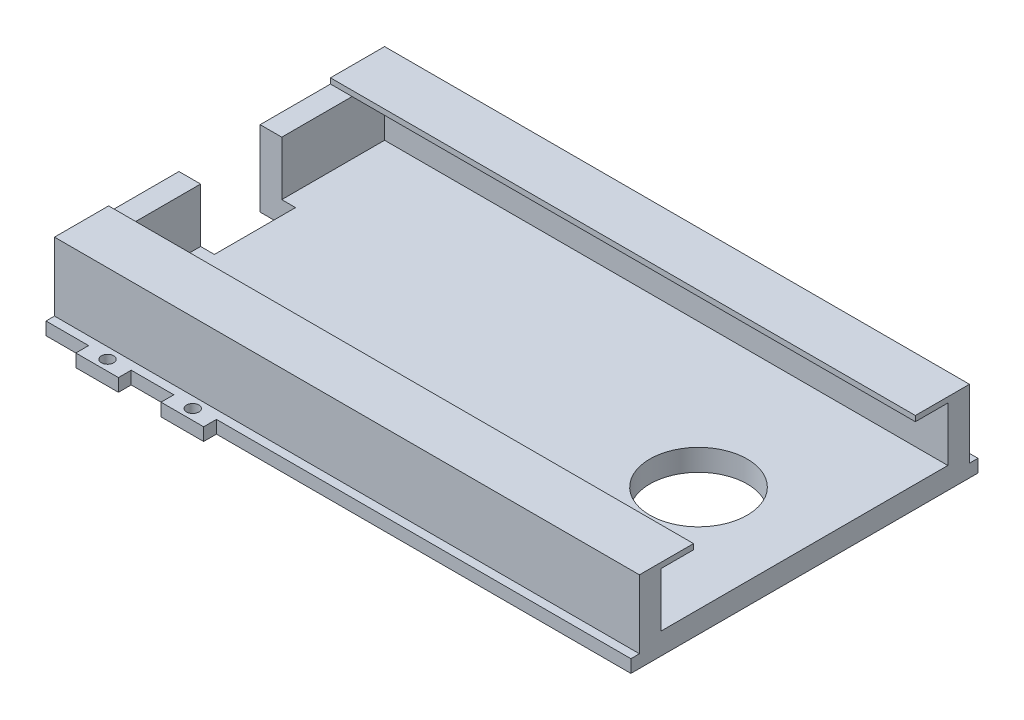
SolidWorks part; units mm, degrees
ref_plane "Front Plane" through (0, 0, 0) normal (0, 0, 1) x (1, 0, 0)
ref_plane "Top Plane" through (0, 0, 0) normal (0, 1, 0) x (1, 0, 0)
ref_plane "Right Plane" through (0, 0, 0) normal (1, 0, 0) x (0, 0, -1)
sketch "Sketch1" plane through (0, 0, 0) normal (0, 1, 0) x (1, 0, 0)
  line L1 (68.6435, -38.735) -> (-68.6435, -38.735)
  line L2 (68.6435, -38.735) -> (68.6435, 38.735)
  line L3 (68.6435, 38.735) -> (-68.6435, 38.735)
  line L4 (-68.6435, -38.735) -> (-68.6435, 38.735)
  line L5 (0, 38.735) -> (0, -38.735) construction
  line L6 (68.6435, 0) -> (-68.6435, 0) construction
  point P0 (0, 0)
extrude "Boss-Extrude1" add sketch "Sketch1" along normal blind 17.78
sketch "Sketch2" plane through (0, 17.78, 0) normal (0, 1, 0) x (1, 0, 0)
  line L0 (68.6435, -38.735) -> (68.6435, 38.735) construction
  line L1 (-63.5635, 33.655) -> (68.6435, 33.655)
  line L2 (-63.5635, 33.655) -> (-63.5635, -33.655)
  line L3 (-63.5635, -33.655) -> (68.6435, -33.655)
  line L4 (68.6435, 33.655) -> (68.6435, -33.655)
  line L5 (-68.6435, 38.735) -> (-68.6435, -38.735) construction
  line L6 (68.6435, 38.735) -> (-68.6435, 38.735) construction
  line L7 (-68.6435, -38.735) -> (68.6435, -38.735) construction
  dimension "D1" = 0
  dimension "D2" = 5.08
  dimension "D3" = 5.08
  dimension "D4" = 5.08
extrude "Cut-Extrude1" cut sketch "Sketch2" against normal blind 12.7
sketch "Sketch4" plane through (0, 5.08, 0) normal (0, 1, 0) x (1, 0, 0)
  line L0 (-63.5635, 33.655) -> (-63.5635, -33.655) construction
  circle A0 centre (43.7769, 0) radius 11.43
  dimension "D1" = 107.3404
extrude "Cut-Extrude2" cut sketch "Sketch4" against normal through all contours A0
sketch "Sketch5" plane through (0, 17.78, 0) normal (0, 1, 0) x (1, 0, 0)
  line L0 (68.6435, -33.655) -> (68.6435, 33.655) construction
  line L1 (-68.6435, 38.735) -> (68.6435, 38.735)
  line L2 (-68.6435, 38.735) -> (-68.6435, 26.035)
  line L3 (-68.6435, 26.035) -> (68.6435, 26.035)
  line L4 (68.6435, 38.735) -> (68.6435, 26.035)
  line L5 (-68.6435, 38.735) -> (-68.6435, -38.735) construction
  line L6 (68.6435, -38.735) -> (-68.6435, -38.735)
  line L7 (68.6435, -38.735) -> (68.6435, -26.035)
  line L8 (68.6435, -26.035) -> (-68.6435, -26.035)
  line L9 (-68.6435, -38.735) -> (-68.6435, -26.035)
  dimension "D1" = 12.7
  dimension "D2" = 12.7
extrude "Boss-Extrude2" add sketch "Sketch5" along normal blind 1.27
sketch "Sketch6" plane through (0, 17.78, 0) normal (0, 1, 0) x (1, 0, 0)
  line L0 (-68.6435, 26.035) -> (-68.6435, -26.035) construction
  line L1 (-68.6435, 9.525) -> (-60.3292, 9.525)
  line L2 (-68.6435, 9.525) -> (-68.6435, -9.525)
  line L3 (-68.6435, -9.525) -> (-60.3292, -9.525)
  line L4 (-60.3292, 9.525) -> (-60.3292, -9.525)
  line L5 (68.6435, 38.735) -> (-68.6435, 38.735) construction
  line L6 (-68.6435, -38.735) -> (68.6435, -38.735) construction
  dimension "D1" = 29.21
  dimension "D2" = 29.21
extrude "Cut-Extrude3" cut sketch "Sketch6" against normal through all
sketch "Sketch9" plane through (0, 0, 0) normal (0, -1, 0) x (-1, 0, 0)
  line L0 (68.6435, -9.525) -> (68.6435, -38.735) construction
  line L1 (-68.6435, -38.735) -> (68.6435, -38.735)
  line L2 (-68.6435, -38.735) -> (-68.6435, -40.735)
  line L3 (-68.6435, -40.735) -> (68.6435, -40.735)
  line L4 (68.6435, -38.735) -> (68.6435, -40.735)
  line L5 (68.6435, 38.735) -> (-68.6435, 38.735)
  line L6 (68.6435, 38.735) -> (68.6435, 40.735)
  line L7 (68.6435, 40.735) -> (-68.6435, 40.735)
  line L8 (-68.6435, 38.735) -> (-68.6435, 40.735)
  line L9 (58.6435, -40.735) -> (48.6435, -40.735)
  line L10 (58.6435, -40.735) -> (58.6435, -43.735)
  line L11 (58.6435, -43.735) -> (48.6435, -43.735)
  line L12 (48.6435, -40.735) -> (48.6435, -43.735)
  line L13 (58.6435, 40.735) -> (48.6435, 40.735)
  line L14 (58.6435, 40.735) -> (58.6435, 43.735)
  line L15 (58.6435, 43.735) -> (48.6435, 43.735)
  line L16 (48.6435, 40.735) -> (48.6435, 43.735)
  line L17 (38.6435, -40.735) -> (28.6435, -40.735)
  line L18 (38.6435, -40.735) -> (38.6435, -43.735)
  line L19 (38.6435, -43.735) -> (28.6435, -43.735)
  line L20 (28.6435, -40.735) -> (28.6435, -43.735)
  line L21 (38.6435, 40.735) -> (28.6435, 40.735)
  line L22 (38.6435, 40.735) -> (38.6435, 43.735)
  line L23 (38.6435, 43.735) -> (28.6435, 43.735)
  line L24 (28.6435, 40.735) -> (28.6435, 43.735)
  dimension "D1" = 2
  dimension "D2" = 2
  dimension "D3" = 10
  dimension "D4" = 10
  dimension "D5" = 10
  dimension "D6" = 10
  dimension "D7" = 10
  dimension "D8" = 10
  dimension "D9" = 10
  dimension "D10" = 10
  dimension "D11" = 3
  dimension "D12" = 3
  dimension "D13" = 3
  dimension "D14" = 3
extrude "Boss-Extrude4" add sketch "Sketch9" against normal blind 3 contours L23 L24 L21 L22 | L7 L8 L5 L6 | L15 L16 L13 L14 | L19 L20 L17 L18 | L11 L12 L9 L10 | L1 L4 L3 L2
sketch "Sketch10" plane through (0, 0, 0) normal (0, -1, 0) x (-1, 0, 0)
  line L0 (58.6435, 43.735) -> (48.6435, 43.735) construction
  line L1 (38.6435, 43.735) -> (28.6435, 43.735) construction
  line L2 (38.6435, -43.735) -> (28.6435, -43.735) construction
  line L3 (58.6435, -43.735) -> (48.6435, -43.735) construction
  line L4 (58.6435, -40.735) -> (58.6435, -43.735) construction
  line L5 (38.6435, -40.735) -> (38.6435, -43.735) construction
  line L6 (38.6435, 40.735) -> (38.6435, 43.735) construction
  line L7 (58.6435, 40.735) -> (58.6435, 43.735) construction
  circle A0 centre (33.6435, -41.295) radius 1.44
  circle A1 centre (53.6435, -41.295) radius 1.44
  circle A2 centre (53.6435, 41.295) radius 1.44
  circle A3 centre (33.6435, 41.295) radius 1.44
  dimension "D1" = 2.44
  dimension "D2" = 2.44
  dimension "D4" = 2.44
  dimension "D5" = 5
  dimension "D6" = 5
  dimension "D7" = 5
  dimension "D8" = 5
  dimension "D3" = 2.44
extrude "Cut-Extrude4" cut sketch "Sketch10" against normal through all
